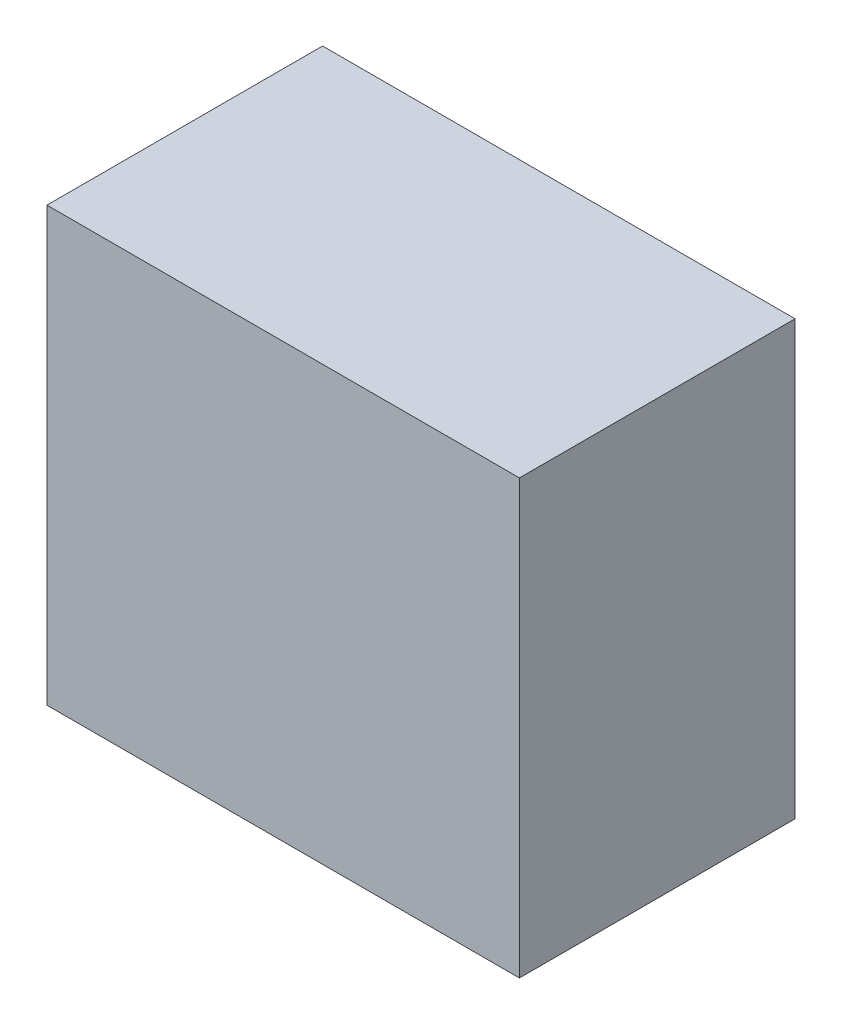
SolidWorks part; units mm, degrees
ref_plane "Front Plane" through (0, 0, 0) normal (0, 0, 1) x (1, 0, 0)
ref_plane "Top Plane" through (0, 0, 0) normal (0, 1, 0) x (1, 0, 0)
ref_plane "Right Plane" through (0, 0, 0) normal (1, 0, 0) x (0, 0, -1)
sketch "Sketch1" plane through (0, 0, 0) normal (0, 0, 1) x (1, 0, 0)
  line L1 (-152.4, 139.7) -> (152.4, 139.7)
  line L2 (-152.4, 139.7) -> (-152.4, -139.7)
  line L3 (-152.4, -139.7) -> (152.4, -139.7)
  line L4 (152.4, 139.7) -> (152.4, -139.7)
  line L5 (-152.4, 139.7) -> (152.4, -139.7) construction
  line L6 (-152.4, -139.7) -> (152.4, 139.7) construction
  point P0 (0, 0)
  dimension "D1" = 279.4
  dimension "D2" = 304.8
extrude "Boss-Extrude1" add sketch "Sketch1" along normal blind 177.8
